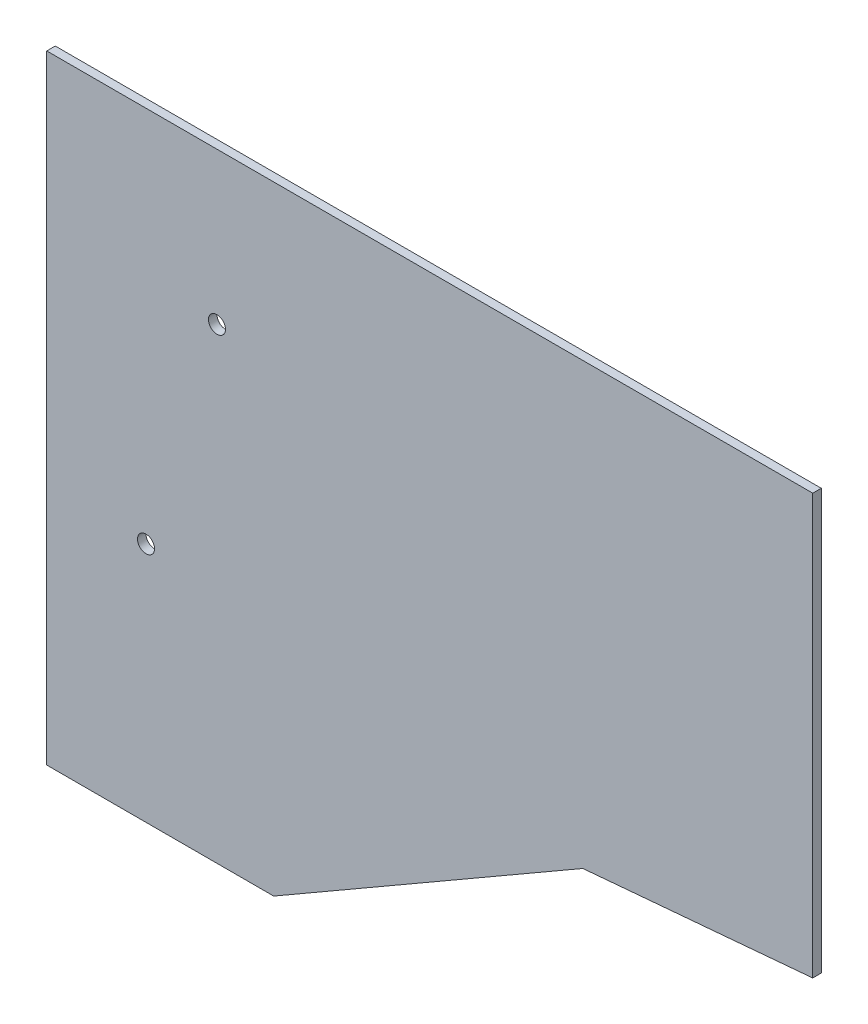
SolidWorks part; units mm, degrees
ref_plane "Plan de face" through (0, 0, 0) normal (0, 0, 1) x (1, 0, 0)
ref_plane "Plan de dessus" through (0, 0, 0) normal (0, 1, 0) x (1, 0, 0)
ref_plane "Plan de droite" through (0, 0, 0) normal (1, 0, 0) x (0, 0, -1)
sketch "Esquisse1" plane through (0, 0, 0) normal (0, 0, 1) x (1, 0, 0)
  line L1 (135, -109) -> (-135, -109)
  line L2 (135, -109) -> (135, 109)
  line L3 (135, 109) -> (-135, 109)
  line L4 (-135, -109) -> (-135, 109)
  line L5 (135, -109) -> (-135, 109) construction
  line L6 (135, 109) -> (-135, -109) construction
  point P0 (0, 0)
extrude "Boss.-Extru.1" add sketch "Esquisse1" along normal blind 3
sketch "Esquisse3" plane through (0, 0, 3) normal (0, 0, 1) x (1, 0, 0)
  line L0 (-135, -109) -> (135, -109) construction
  line L1 (-135, 109) -> (-135, -109) construction
  circle A0 centre (-100, -24) radius 3
  dimension "D1" = 85
  dimension "D2" = 35
extrude "Enlèv. mat.-Extru.1" cut sketch "Esquisse3" against normal blind 10
sketch "Esquisse4" plane through (0, 0, 3) normal (0, 0, 1) x (1, 0, 0)
  line L0 (135, 109) -> (-135, 109) construction
  line L3 (-135, 109) -> (-135, -109) construction
  circle A0 centre (-75, 55.5) radius 3
  dimension "D1" = 53.5
  dimension "D2" = 60
extrude "Enlèv. mat.-Extru.2" cut sketch "Esquisse4" against normal blind 10
sketch "Esquisse5" plane through (0, 0, 3) normal (0, 0, 1) x (1, 0, 0)
  line L0 (53.9637, -46.0898) -> (135, -39)
  line L1 (53.9637, -46.0898) -> (-55, -109)
  line L3 (135, -109) -> (135, 109) construction
  line L4 (-135, -109) -> (135, -109) construction
  dimension "D1" = 80
  dimension "D2" = 95
  dimension "D3" = 0
  dimension "D4" = 150
  dimension "D5" = 70
  dimension "D6" = 0
extrude "Enlèv. mat.-Extru.11" cut sketch "Esquisse5" against normal through all and the other way through all
